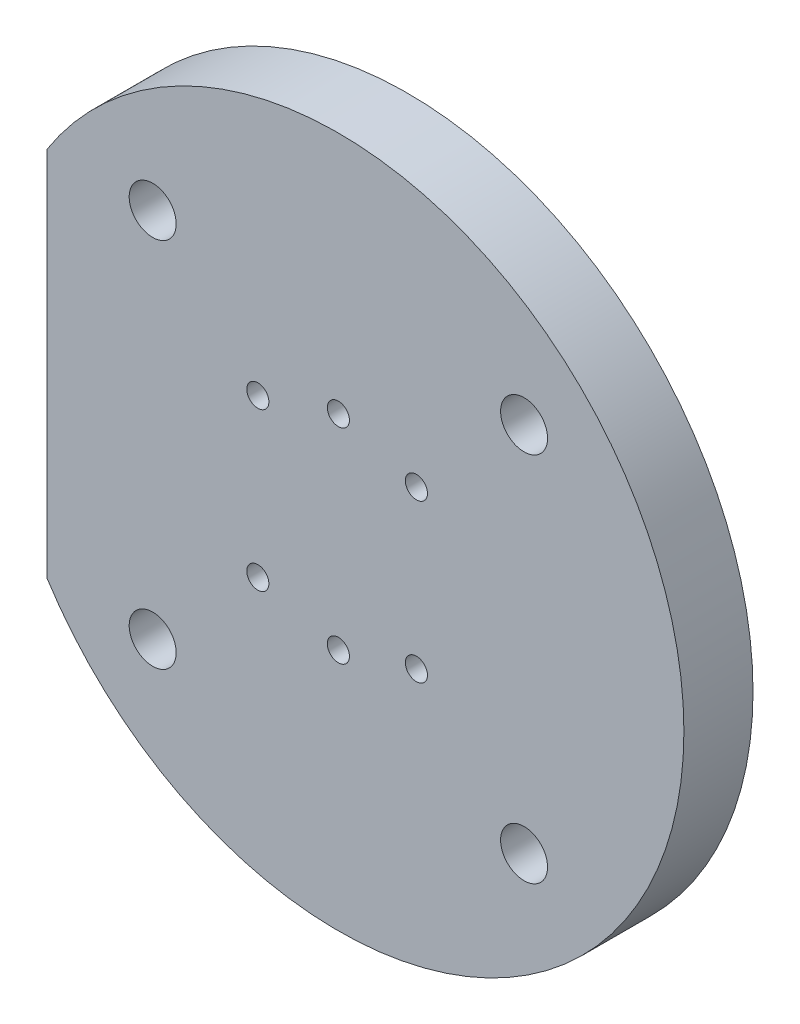
SolidWorks part; units mm, degrees
ref_plane "Plan de face" through (0, 0, 0) normal (0, 0, 1) x (1, 0, 0)
ref_plane "Plan de dessus" through (0, 0, 0) normal (0, 1, 0) x (1, 0, 0)
ref_plane "Plan de droite" through (0, 0, 0) normal (1, 0, 0) x (0, 0, -1)
sketch "Esquisse1" plane through (0, 0, 0) normal (0, 0, 1) x (1, 0, 0)
  circle A0 centre (0, 0) radius 25
  circle A1 centre (-13.435, 13.435) radius 1.7
  circle A2 centre (13.435, 13.435) radius 1.7
  circle A3 centre (13.435, -13.435) radius 1.7
  circle A4 centre (-13.435, -13.435) radius 1.7
  point P19 (0, 0)
  dimension "D1" = 50
  dimension "D5" = 19
  dimension "D6" = 3.4
  dimension "D4" = 4
extrude "Boss.-Extru.1" add sketch "Esquisse1" along normal blind 5
ref_plane "Plan1" through (0, 0, 0) normal (1, 0, 0) x (0, 0, -1)
sketch "Esquisse6" plane through (0, 0, 0) normal (0, 0, -1) x (-1, 0, 0)
  circle A0 centre (0, 0) radius 11
  dimension "D1" = 22
sketch "Esquisse8" plane through (0, 0, 5) normal (0, 0, 1) x (1, 0, 0)
  line L0 (-6.5, 2) -> (6.5, 2) construction
  line L1 (6.5, 2) -> (6.5, -2) construction
  line L2 (6.5, -2) -> (-6.5, -2) construction
  line L3 (-6.5, 2) -> (-6.5, -2) construction
  line L4 (-6.25, 1.75) -> (-6.25, 2) construction
  line L5 (-6.25, 1.75) -> (-6.5, 1.75) construction
  line L6 (-6.25, -1.75) -> (-6.5, -1.75) construction
  line L7 (-6.25, -1.75) -> (-6.25, -2) construction
  line L8 (6.25, 1.75) -> (6.25, 2) construction
  line L9 (6.25, 1.75) -> (6.5, 1.75) construction
  line L10 (6.25, -1.75) -> (6.5, -1.75) construction
  line L11 (6.25, -1.75) -> (6.25, -2) construction
  line L12 (6.5, 0) -> (-6.5, 0) construction
  circle A0 centre (-6.25, 1.75) radius 0.25
  circle A1 centre (-6.25, -1.75) radius 0.25
  circle A2 centre (6.25, 1.75) radius 0.25
  circle A3 centre (6.25, -1.75) radius 0.25
sketch "Esquisse10" plane through (0, 0, 5) normal (0, 0, 1) x (1, 0, 0)
  line L0 (-10, 0) -> (10, 0) construction
  line L1 (10, 0) -> (10, 5) construction
  line L2 (10, 5) -> (-10, 5) construction
  line L3 (-10, 5) -> (-10, 0) construction
  line L4 (6.5, -2) -> (-6.5, -2) construction
  line L5 (-6.5, 2) -> (6.5, 2) construction
  line L6 (6.5, 2) -> (6.5, -2) construction
  line L7 (6.5, 0) -> (-6.5, 0) construction
  line L8 (9.2495, -0.5365) -> (9.2495, 3.4635) construction
  line L9 (10, 0) -> (10, -5) construction
  line L10 (10, -5) -> (-10, -5) construction
  line L11 (-10, -5) -> (-10, 0) construction
  line L12 (-6.25, -1.75) -> (-10, -5) construction
  line L13 (-5.7588, -2.3168) -> (-9.5088, -5.5668)
  line L14 (-6.7412, -1.1832) -> (-10.4912, -4.4332)
  line L15 (-6.25, 1.75) -> (-10, 5) construction
  line L16 (-6.7412, 1.1832) -> (-10.4912, 4.4332)
  line L17 (-5.7588, 2.3168) -> (-9.5088, 5.5668)
  line L18 (10, -5) -> (6.25, -1.75) construction
  line L19 (9.5088, -5.5668) -> (5.7588, -2.3168)
  line L20 (10.4912, -4.4332) -> (6.7412, -1.1832)
  line L21 (10, 5) -> (6.25, 1.75) construction
  line L22 (10.4912, 4.4332) -> (6.7412, 1.1832)
  line L23 (9.5088, 5.5668) -> (5.7588, 2.3168)
  arc A0 (-5.7588, -2.3168) -> (-6.7412, -1.1832) centre (-6.25, -1.75) ccw
  arc A1 (-10.4912, -4.4332) -> (-9.5088, -5.5668) centre (-10, -5) ccw
  arc A2 (-6.7412, 1.1832) -> (-5.7588, 2.3168) centre (-6.25, 1.75) ccw
  arc A3 (-9.5088, 5.5668) -> (-10.4912, 4.4332) centre (-10, 5) ccw
  arc A4 (9.5088, -5.5668) -> (10.4912, -4.4332) centre (10, -5) ccw
  arc A5 (6.7412, -1.1832) -> (5.7588, -2.3168) centre (6.25, -1.75) ccw
  arc A6 (10.4912, 4.4332) -> (9.5088, 5.5668) centre (10, 5) ccw
  arc A7 (5.7588, 2.3168) -> (6.7412, 1.1832) centre (6.25, 1.75) ccw
  point P12 (0, 0)
  point P18 (-8.125, -3.375)
  point P24 (-8.125, 3.375)
  point P31 (8.125, -3.375)
  point P38 (8.125, 3.375)
sketch "Esquisse11" plane through (0, 0, 0) normal (0, 0, -1) x (-1, 0, 0)
  line L1 (5.8275, 5.6343) -> (-5.6451, 5.6343) construction
  line L2 (5.8275, 5.6343) -> (5.8275, -5.7587) construction
  line L3 (5.8275, -5.7587) -> (-5.6451, -5.7587) construction
  line L4 (-5.6451, 5.6343) -> (-5.6451, -5.7587) construction
  circle A0 centre (0, 7.3989) radius 0.8
  circle A1 centre (5.8275, 5.6343) radius 0.8
  circle A2 centre (5.8275, -5.7587) radius 0.8
  circle A3 centre (0, -7.3989) radius 0.8
  circle A4 centre (-5.6451, -5.7587) radius 0.8
  circle A5 centre (-5.6451, 5.6343) radius 0.8
  ellipse E0 centre (0, 0) end of major axis (8.9909, 0) minor radius 7.3989 construction
extrude "Enlèv. mat.-Extru.1" cut sketch "Esquisse11" against normal through all
sketch "Esquisse13" plane through (0, 0, 0) normal (0, 0, -1) x (-1, 0, 0)
  line L1 (21.0832, 13.435) -> (25.9868, 13.435)
  line L2 (21.0832, 13.435) -> (21.0832, -15.4591)
  line L3 (21.0832, -15.4591) -> (25.9868, -15.4591)
  line L4 (25.9868, 13.435) -> (25.9868, -15.4591)
  circle A0 centre (0, 0) radius 25 construction
extrude "Enlèv. mat.-Extru.2" cut sketch "Esquisse13" against normal through all
equation "\"9.5.00mm\"=6"
